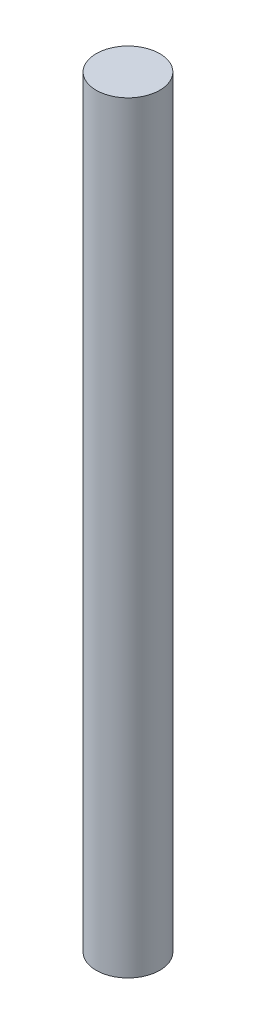
SolidWorks part; units mm, degrees
ref_plane "Front Plane" through (0, 0, 0) normal (0, 0, 1) x (1, 0, 0)
ref_plane "Top Plane" through (0, 0, 0) normal (0, 1, 0) x (1, 0, 0)
ref_plane "Right Plane" through (0, 0, 0) normal (1, 0, 0) x (0, 0, -1)
sketch "Sketch1" plane through (0, 0, 0) normal (0, 1, 0) x (1, 0, 0)
  circle A0 centre (0, 0) radius 1.1906
extrude "Boss-Extrude1" add sketch "Sketch1" along normal blind 28.575
